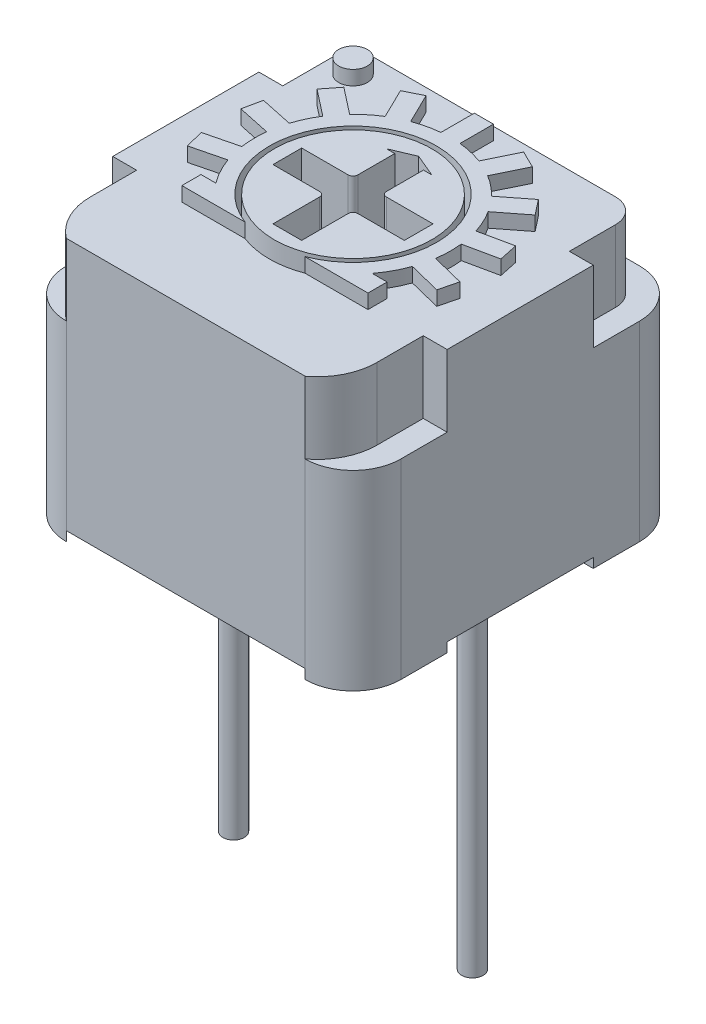
SolidWorks part; units mm, degrees
ref_plane "Front Plane" through (0, 0, 0) normal (0, 0, 1) x (1, 0, 0)
ref_plane "Top Plane" through (0, 0, 0) normal (0, 1, 0) x (1, 0, 0)
ref_plane "Right Plane" through (0, 0, 0) normal (1, 0, 0) x (0, 0, -1)
sketch "Sketch1" plane through (0, 0, 0) normal (0, 1, 0) x (1, 0, 0)
  line L1 (2.5, -3.5) -> (-2.5, -3.5)
  line L2 (3.5, -2.5) -> (3.5, 2.5)
  line L3 (2.5, 3.5) -> (-2.5, 3.5)
  line L4 (-3.5, -2.5) -> (-3.5, 2.5)
  line L5 (3.5, -3.5) -> (-3.5, 3.5) construction
  line L6 (3.5, 3.5) -> (-3.5, -3.5) construction
  arc A0 (-2.5, 3.5) -> (-3.5, 2.5) centre (-2.5, 2.5) ccw
  arc A1 (3.5, 2.5) -> (2.5, 3.5) centre (2.5, 2.5) ccw
  arc A2 (3.5, -2.5) -> (2.5, -3.5) centre (2.5, -2.5) cw
  arc A3 (-2.5, -3.5) -> (-3.5, -2.5) centre (-2.5, -2.5) cw
  point P0 (0, 0)
  dimension "D2" = 1
  dimension "D3" = 1
  dimension "D4" = 1
  dimension "D1" = 7
extrude "Boss-Extrude1" add sketch "Sketch1" along normal blind 5.5
sketch "Sketch3" plane through (0, 5.5, 0) normal (0, 1, 0) x (1, 0, 0)
  circle A0 centre (0, 0) radius 1.75
  dimension "D1" = 3.5
extrude "Cut-Extrude1" cut sketch "Sketch3" against normal blind 1.75
sketch "Sketch4" plane through (0, 3.75, 0) normal (0, 1, 0) x (1, 0, 0)
  circle A0 centre (0, 0) radius 1.65
  circle A1 centre (0, 0) radius 1.75 construction
  dimension "D1" = 0.1
extrude "Boss-Extrude2" add sketch "Sketch4" along normal offset from surface (2.05 mm away) 5.8 separate body up to face at (0, 0, 0)
sketch "Sketch5" plane through (0, 5.8, 0) normal (0, 1, 0) x (1, 0, 0)
  line L0 (-0.3, 0.3) -> (-0.3, 1.175)
  line L1 (1.375, -0.3) -> (0.3, -0.3)
  line L2 (1.375, -0.3) -> (1.375, 0.3)
  line L3 (1.375, 0.3) -> (0.3, 0.3)
  line L4 (-1.375, -0.3) -> (-1.375, 0.3)
  line L5 (1.375, -0.3) -> (-1.375, 0.3) construction
  line L6 (1.375, 0.3) -> (-1.375, -0.3) construction
  line L7 (0.3, -1.375) -> (-0.3, -1.375)
  line L8 (0.3, -1.375) -> (0.3, -0.3)
  line L10 (-0.3, -1.375) -> (-0.3, -0.3)
  line L11 (0.3, -1.375) -> (-0.2748, 1.2593) construction
  line L12 (0.2748, 1.2593) -> (-0.3, -1.375) construction
  line L13 (-0.3, -0.3) -> (-1.375, -0.3)
  line L14 (0.3, 0.3) -> (0.3, 1.175)
  line L15 (-0.3, 0.3) -> (-1.375, 0.3)
  line L16 (0, 1.375) -> (-0.475, 1.175)
  line L17 (-0.475, 1.175) -> (-0.3, 1.175)
  line L18 (0.475, 1.175) -> (0, 1.375)
  line L19 (-0.3, 0.3) -> (0.3, 0.3) construction
  line L20 (0.3, 1.175) -> (0.475, 1.175)
  line L21 (0, 0.3) -> (0, 1.375) construction
  point P0 (0, 0)
  point P6 (0, 0)
  dimension "D1" = 2.75
  dimension "D2" = 0.6
  dimension "D3" = 0.95
  dimension "D4" = 0.2
extrude "Cut-Extrude2" cut sketch "Sketch5" against normal blind 1.6
fillet "Fillet1" radius 0.1 4 edges at (0.3, 5, 0.3) (-0.3, 5, 0.3) (0.3, 5, -0.3) (-0.3, 5, -0.3)
sketch "Sketch6" plane through (0, 5.5, 0) normal (0, 1, 0) x (1, 0, 0)
  line L0 (-0.625, -1.6346) -> (-1.948, -1.6346)
  line L1 (-1.948, -1.6346) -> (-1.948, -1.2346)
  line L2 (-1.948, -1.2346) -> (-1.6365, -1.2346)
  line L3 (0.625, -1.6346) -> (1.948, -1.6346)
  line L4 (1.948, -1.6346) -> (1.948, -1.2346)
  line L5 (1.948, -1.2346) -> (1.6365, -1.2346)
  line L6 (-1.948, -1.6346) -> (0, 0) construction
  line L7 (0, 0) -> (1.948, -1.6346) construction
  line L8 (-1.9312, -0.6876) -> (-2.6104, -0.857)
  line L9 (-2.6104, -0.857) -> (-2.7072, -0.4689)
  line L10 (-2.7072, -0.4689) -> (-2.028, -0.2995)
  line L11 (-2.7219, 0.3741) -> (-2.0372, 0.2286)
  line L12 (-2.7219, 0.3741) -> (-2.6388, 0.7654)
  line L13 (-2.6388, 0.7654) -> (-1.9541, 0.6198)
  line L14 (-2.2825, 1.5294) -> (-1.7308, 1.0985)
  line L15 (-2.2825, 1.5294) -> (-2.0362, 1.8447)
  line L16 (-2.0362, 1.8447) -> (-1.4846, 1.4137)
  line L17 (-1.381, 2.3752) -> (-1.0741, 1.7461)
  line L18 (-1.381, 2.3752) -> (-1.0215, 2.5506)
  line L19 (-1.0215, 2.5506) -> (-0.7146, 1.9214)
  line L20 (-0.2, 2.0402) -> (-0.2, 2.7402)
  line L21 (-0.2, 2.7402) -> (0.2, 2.7402)
  line L22 (0.2, 2.7402) -> (0.2, 2.0402)
  line L23 (0, 0) -> (0, 2.7402) construction
  line L24 (-2.6588, -0.6629) -> (0, 0) construction
  line L25 (0, 0) -> (-2.6803, 0.5697) construction
  line L26 (0, 0) -> (-2.1593, 1.687) construction
  line L27 (0, 0) -> (-1.2012, 2.4629) construction
  line L28 (1.0215, 2.5506) -> (0.7146, 1.9214)
  line L29 (1.381, 2.3752) -> (1.0215, 2.5506)
  line L30 (1.381, 2.3752) -> (1.0741, 1.7461)
  line L31 (2.0362, 1.8447) -> (1.4846, 1.4137)
  line L32 (2.2825, 1.5294) -> (2.0362, 1.8447)
  line L33 (2.2825, 1.5294) -> (1.7308, 1.0985)
  line L34 (2.6388, 0.7654) -> (1.9541, 0.6198)
  line L35 (2.7219, 0.3741) -> (2.6388, 0.7654)
  line L36 (2.7219, 0.3741) -> (2.0372, 0.2286)
  line L37 (2.7072, -0.4689) -> (2.028, -0.2995)
  line L38 (2.6104, -0.857) -> (2.7072, -0.4689)
  line L39 (1.9312, -0.6876) -> (2.6104, -0.857)
  arc A0 (-0.625, -1.6346) -> (0.625, -1.6346) centre (0, 0) cw
  circle A1 centre (0, 0) radius 1.75 construction
  arc A2 (-1.6365, -1.2346) -> (-1.9312, -0.6876) centre (0, 0) cw
  arc A3 (-2.028, -0.2995) -> (-2.0372, 0.2286) centre (0, 0) cw
  arc A4 (-1.9541, 0.6198) -> (-1.7308, 1.0985) centre (0, 0) cw
  arc A5 (-1.4846, 1.4137) -> (-1.0741, 1.7461) centre (0, 0) cw
  arc A6 (-0.7146, 1.9214) -> (-0.2, 2.0402) centre (0, 0) cw
  arc A7 (0.2, 2.0402) -> (0.7146, 1.9214) centre (0, 0) cw
  arc A8 (1.0741, 1.7461) -> (1.4846, 1.4137) centre (0, 0) cw
  arc A9 (1.9312, -0.6876) -> (1.6365, -1.2346) centre (0, 0) cw
  arc A10 (2.0372, 0.2286) -> (2.028, -0.2995) centre (0, 0) cw
  arc A11 (1.7308, 1.0985) -> (1.9541, 0.6198) centre (0, 0) cw
  dimension "D1" = 0.3
  dimension "D2" = 1.25
  dimension "D3" = 260
  dimension "D4" = 0.4
  dimension "D5" = 26
  dimension "D6" = 52
  dimension "D7" = 78
  dimension "D8" = 104
  dimension "D9" = 0.7
extrude "Boss-Extrude3" add sketch "Sketch6" along normal up to surface (0.3 mm away) up to face at (0, 5.8, -0.175)
sketch "Sketch7" plane through (0, 5.5, 0) normal (0, 1, 0) x (1, 0, 0)
  line L0 (0, 0) -> (-2.4749, 2.4749) construction
  line L1 (-2.4749, 2.4749) -> (0, 0) construction
  line L2 (0, 0) -> (0, 3.5) construction
  line L3 (2.5, 3.5) -> (-2.5, 3.5) construction
  circle A0 centre (-2.4749, 2.4749) radius 0.3
  dimension "D1" = 0.6
  dimension "D2" = 45
  dimension "D3" = 3.5
extrude "Boss-Extrude4" add sketch "Sketch7" along normal up to surface (0.3 mm away) up to face at (0, 5.8, -0.6779)
sketch "Sketch2" plane through (0, 5.5, 0) normal (0, 1, 0) x (1, 0, 0)
  line L0 (3.5, -2.5) -> (3.5, 2.5) construction
  line L1 (-2.5, -3.5) -> (2.5, -3.5) construction
  line L2 (2.5, 3.5) -> (-2.5, 3.5) construction
  line L3 (-3.5, 2.5) -> (-3.5, -2.5) construction
  line L4 (3.5, -2.5) -> (3.5, 2.5)
  line L5 (-2.5, -3.5) -> (2.5, -3.5)
  line L6 (2.5, 3.5) -> (-2.5, 3.5)
  line L7 (-3.5, 2.5) -> (-3.5, -2.5)
  line L8 (-3.5, 1.5294) -> (-3, 1.5294)
  line L9 (-3, 1.5294) -> (-3, 3)
  line L10 (-3, 3) -> (3, 3)
  line L11 (3, 3) -> (3, 1.5294)
  line L12 (3, 1.5294) -> (3.5, 1.5294)
  line L13 (0, 3) -> (0, 3.5) construction
  line L14 (-3.5, -1.5294) -> (-3, -1.5294)
  line L15 (-3, -1.5294) -> (-3, -2.5)
  line L16 (-3, -1.5294) -> (-3, 1.5294) construction
  line L17 (3.5, -1.5294) -> (3, -1.5294)
  line L18 (3, -1.5294) -> (3, -2.5)
  arc A0 (2.5, -3.5) -> (3.5, -2.5) centre (2.5, -2.5) ccw construction
  arc A1 (-3.5, -2.5) -> (-2.5, -3.5) centre (-2.5, -2.5) ccw construction
  arc A2 (3.5, 2.5) -> (2.5, 3.5) centre (2.5, 2.5) ccw construction
  arc A3 (-2.5, 3.5) -> (-3.5, 2.5) centre (-2.5, 2.5) ccw construction
  arc A4 (2.5, -3.5) -> (3.5, -2.5) centre (2.5, -2.5) ccw
  arc A5 (-3.5, -2.5) -> (-2.5, -3.5) centre (-2.5, -2.5) ccw
  arc A6 (3.5, 2.5) -> (2.5, 3.5) centre (2.5, 2.5) ccw
  arc A7 (-2.5, 3.5) -> (-3.5, 2.5) centre (-2.5, 2.5) ccw
  arc A8 (-3, -2.5) -> (-2.5, -3.5) centre (-1.75, -2.5) ccw
  arc A9 (2.5, -3.5) -> (3, -2.5) centre (1.75, -2.5) ccw
  point P25 (-3, 0)
  dimension "D1" = 0.5
extrude "Cut-Extrude3" cut sketch "Sketch2" against normal blind 1.5 contours A8 L15 L14 L7 A5 | A9 A4 L4 L17 L18 | L6 A7 L7 L8 L9 L10 L11 L12 L4 A6
fillet "Fillet2" radius 0.5 2 edges at (3, 4.75, -3) (-3, 4.75, -3)
sketch "Sketch10" plane through (0, 0, 0) normal (0, 1, 0) x (1, 0, 0)
  line L0 (3.5, -2.5) -> (3.5, -1.5294) construction
  line L1 (3.5, -1.5294) -> (3, -1.5294) construction
  line L2 (3, -1.5294) -> (3, -2.5) construction
  line L3 (-3, -2.5) -> (-3, -1.5294) construction
  line L4 (-3, -1.5294) -> (-3.5, -1.5294) construction
  line L5 (-3.5, -1.5294) -> (-3.5, -2.5) construction
  line L6 (2.5, 3.5) -> (-2.5, 3.5) construction
  line L7 (-3.5, 2.5) -> (-3.5, 1.5294) construction
  line L8 (-3.5, 1.5294) -> (-3, 1.5294) construction
  line L9 (-3, 1.5294) -> (-3, 2.5) construction
  line L10 (-2.5, 3) -> (2.5, 3) construction
  line L11 (3, 2.5) -> (3, 1.5294) construction
  line L12 (3, 1.5294) -> (3.5, 1.5294) construction
  line L13 (3.5, 1.5294) -> (3.5, 2.5) construction
  line L14 (3.5, -2.5) -> (3.5, -1.5294)
  line L15 (3.5, -1.5294) -> (3, -1.5294)
  line L16 (3, -1.5294) -> (3, -2.5)
  line L17 (-3, -2.5) -> (-3, -1.5294)
  line L18 (-3, -1.5294) -> (-3.5, -1.5294)
  line L19 (-3.5, -1.5294) -> (-3.5, -2.5)
  line L20 (2.5, 3.5) -> (-2.5, 3.5)
  line L21 (-3.5, 2.5) -> (-3.5, 1.5294)
  line L22 (-3.5, 1.5294) -> (-3, 1.5294)
  line L23 (-3, 1.5294) -> (-3, 2.5)
  line L24 (-2.5, 3) -> (2.5, 3)
  line L25 (3, 2.5) -> (3, 1.5294)
  line L26 (3, 1.5294) -> (3.5, 1.5294)
  line L27 (3.5, 1.5294) -> (3.5, 2.5)
  line L28 (-2.5, -3.5) -> (2.5, -3.5)
  line L29 (3.5, -1.5294) -> (3.5, 1.5294)
  line L30 (-3.5, -1.5294) -> (-3.5, 1.5294)
  arc A0 (2.5, -3.5) -> (3, -2.5) centre (1.75, -2.5) ccw construction
  arc A1 (2.5, -3.5) -> (3.5, -2.5) centre (2.5, -2.5) ccw construction
  arc A2 (-3, -2.5) -> (-2.5, -3.5) centre (-1.75, -2.5) ccw construction
  arc A3 (-3.5, -2.5) -> (-2.5, -3.5) centre (-2.5, -2.5) ccw construction
  arc A4 (-2.5, 3.5) -> (-3.5, 2.5) centre (-2.5, 2.5) ccw construction
  arc A5 (-2.5, 3) -> (-3, 2.5) centre (-2.5, 2.5) ccw construction
  arc A6 (3, 2.5) -> (2.5, 3) centre (2.5, 2.5) ccw construction
  arc A7 (3.5, 2.5) -> (2.5, 3.5) centre (2.5, 2.5) ccw construction
  arc A8 (2.5, -3.5) -> (3, -2.5) centre (1.75, -2.5) ccw
  arc A9 (2.5, -3.5) -> (3.5, -2.5) centre (2.5, -2.5) ccw
  arc A10 (-3, -2.5) -> (-2.5, -3.5) centre (-1.75, -2.5) ccw
  arc A11 (-3.5, -2.5) -> (-2.5, -3.5) centre (-2.5, -2.5) ccw
  arc A12 (-2.5, 3.5) -> (-3.5, 2.5) centre (-2.5, 2.5) ccw
  arc A13 (-2.5, 3) -> (-3, 2.5) centre (-2.5, 2.5) ccw
  arc A14 (3, 2.5) -> (2.5, 3) centre (2.5, 2.5) ccw
  arc A15 (3.5, 2.5) -> (2.5, 3.5) centre (2.5, 2.5) ccw
extrude "Cut-Extrude7" cut sketch "Sketch10" along normal blind 0.2 contours L25 A14 L24 A13 L23 L22 L30 L18 L17 A10 L28 A8 L16 L15 L29 L26
sketch "Sketch11" plane through (0, 0.2, 0) normal (0, -1, 0) x (1, 0, 0)
  line L0 (3.5, 0) -> (2.5, 0) construction
  line L1 (3.5, 1.5294) -> (3.5, -1.5294) construction
  line L2 (2.5, 0) -> (0, 0) construction
  line L3 (-2.5, 0) -> (-3.5, 0) construction
  line L4 (-3.5, 1.5294) -> (-3.5, -1.5294) construction
  line L5 (0, 0) -> (0, -2.5) construction
  line L6 (0, 0) -> (-2.5, 0) construction
  circle A0 centre (2.5, 0) radius 0.225
  circle A1 centre (0, -2.5) radius 0.225
  circle A2 centre (-2.5, 0) radius 0.225
  dimension "D1" = 0.45
  dimension "D2" = 2.5
extrude "Boss-Extrude6" add sketch "Sketch11" along normal blind 7.2 separate body
